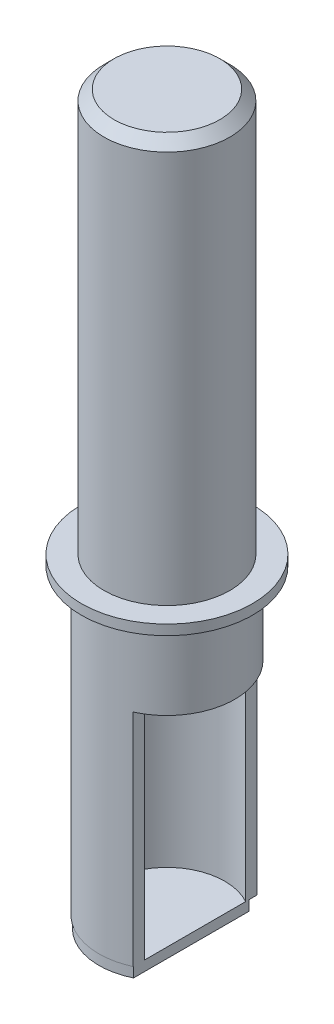
SolidWorks part; units mm, degrees
ref_plane "Front Plane" through (0, 0, 0) normal (0, 0, 1) x (1, 0, 0)
ref_plane "Top Plane" through (0, 0, 0) normal (0, 1, 0) x (1, 0, 0)
ref_plane "Right Plane" through (0, 0, 0) normal (1, 0, 0) x (0, 0, -1)
sketch "Sketch1" plane through (0, 0, 0) normal (0, 1, 0) x (1, 0, 0)
  circle A0 centre (0, 0) radius 13.5
  circle A1 centre (0, 0) radius 11.5
  dimension "D1" = 27
  dimension "D2" = 2
extrude "Boss-Extrude1" add sketch "Sketch1" along normal blind 60
sketch "Sketch2" plane through (0, 0, 0) normal (0, -1, 0) x (1, 0, 0)
  circle A0 centre (0, 0.7382) radius 12.7618
extrude "Boss-Extrude2" add sketch "Sketch2" along normal blind 2
sketch "Sketch3" plane through (0, 0, 0) normal (0, 0, 1) x (1, 0, 0)
  line L1 (26.7265, -8.2314) -> (5.574, -8.2314)
  line L2 (26.7265, -8.2314) -> (26.7265, 43.7925)
  line L3 (26.7265, 43.7925) -> (5.574, 43.7925)
  line L4 (5.574, -8.2314) -> (5.574, 43.7925)
extrude "Cut-Extrude1" cut sketch "Sketch3" against normal through all and the other way through all
sketch "Sketch4" plane through (0, 60, 0) normal (0, 1, 0) x (1, 0, 0)
  circle A0 centre (0, 0) radius 17
  circle A1 centre (0, 0) radius 3
  dimension "D1" = 34
  dimension "D2" = 6
extrude "Boss-Extrude3" add sketch "Sketch4" along normal blind 2
sketch "Sketch5" plane through (0, 62, 0) normal (0, 1, 0) x (1, 0, 0)
  circle A0 centre (0, 0) radius 12.5
  dimension "D1" = 25
extrude "Boss-Extrude4" add sketch "Sketch5" along normal blind 80
chamfer "Chamfer1" distance 2 angle 45 1 edges at (0, 142, 12.5)
